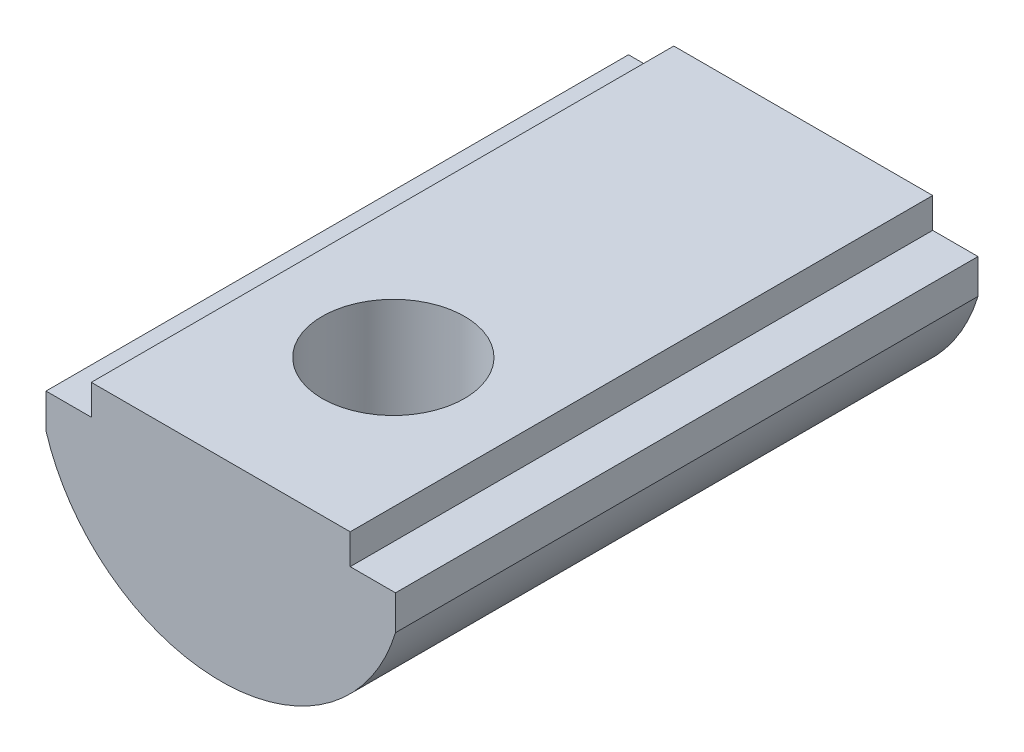
SolidWorks part; units mm, degrees
ref_plane "Plan de face" through (0, 0, 0) normal (0, 0, 1) x (1, 0, 0)
ref_plane "Plan de dessus" through (0, 0, 0) normal (0, 1, 0) x (1, 0, 0)
ref_plane "Plan de droite" through (0, 0, 0) normal (1, 0, 0) x (0, 0, -1)
sketch "Esquisse1" plane through (0, 0, 0) normal (0, 0, 1) x (1, 0, 0)
  line L0 (-3, 0) -> (3, 0)
  line L1 (3, 0) -> (3, -0.7)
  line L2 (3, -0.7) -> (4.05, -0.7)
  line L3 (4.05, -0.7) -> (4.05, -1.5)
  line L4 (0, 0) -> (0, -4.5) construction
  line L5 (-4.05, -0.7) -> (-4.05, -1.5)
  line L6 (-3, -0.7) -> (-4.05, -0.7)
  line L7 (-3, 0) -> (-3, -0.7)
  arc A0 (4.05, -1.5) -> (-4.05, -1.5) centre (0, -0.2662) cw
  dimension "D1" = 8.1
  dimension "D2" = 6
  dimension "D3" = 0.7
  dimension "D4" = 4.5
  dimension "D5" = 0.8
extrude "Boss.-Extru.1" add sketch "Esquisse1" along normal blind 13.5
hole_wizard "Trou pour taraudage pour trou taraudé M41" positions "Esquisse2" profile "Esquisse3" hole size "M4" standard "DIN" end condition through all
sketch "Esquisse2" plane through (0, 0, 0) normal (0, 1, 0) x (1, 0, 0)
  line L0 (3, -13.5) -> (-3, -13.5) construction
  point P0 (0, -9.5)
  dimension "D1" = 4
sketch "Esquisse3" plane through (0, 0, 9.5) normal (1, 0, 0) x (0, 0, 1)
  line L0 (0, 0) -> (0, 4.5)
  line L1 (0, 4.5) -> (1.65, 4.5)
  line L2 (1.65, 4.5) -> (1.65, 0)
  line L5 (1.65, 0) -> (0, 0)
  line L11 (0, -6.35) -> (0, 107.95) construction
  dimension "Diamètre du perçage jusqu'au prochain" = 3.3
  dimension "Profondeur du perçage jusqu'au prochain" = 4.5
sketch "Esquisse4" plane through (0, 0, 0) normal (1, 0, 0) x (0, 0, -1)
  line L1 (0, -4.5) -> (0, -1.5) construction
  line L2 (-3, -3.3) -> (-3, -5.3)
  line L3 (-7.85, -4.5) -> (0, -4.5) construction
  arc A0 (-3, -5.3) -> (-3, -3.3) centre (-3, -4.3) ccw
  dimension "D1" = 2
  dimension "D2" = 3
  dimension "D3" = 0.8
revolve "Révolution1" add sketch "Esquisse4" angle 360 about L2
